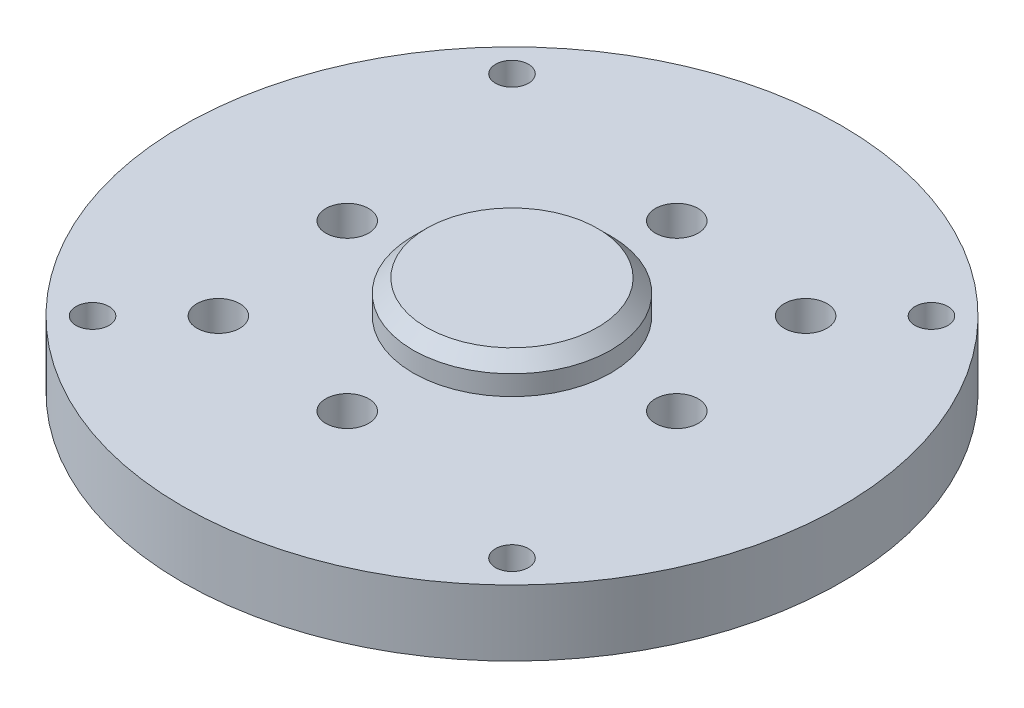
SolidWorks part; units mm, degrees
ref_plane "Front Plane" through (0, 0, 0) normal (0, 0, 1) x (1, 0, 0)
ref_plane "Top Plane" through (0, 0, 0) normal (0, 1, 0) x (1, 0, 0)
ref_plane "Right Plane" through (0, 0, 0) normal (1, 0, 0) x (0, 0, -1)
sketch "Sketch1" plane through (0, 0, 0) normal (0, 1, 0) x (1, 0, 0)
  line L1 (-50, -50) -> (50, -50)
  line L2 (-50, -50) -> (-50, 50)
  line L3 (-50, 50) -> (50, 50)
  line L4 (50, -50) -> (50, 50)
  line L5 (-50, -50) -> (50, 50) construction
  line L6 (-50, 50) -> (50, -50) construction
  point P0 (0, 0)
  dimension "D1" = 100
  dimension "D2" = 100
extrude "Boss-Extrude1" add sketch "Sketch1" along normal blind 10
sketch "Sketch2" plane through (0, 10, 0) normal (0, 1, 0) x (1, 0, 0)
  line L0 (0, 0) -> (-50, 0) construction
  line L1 (-50, 50) -> (-50, -50) construction
  line L2 (0, 0) -> (-25, 0) construction
  line L3 (0, 0) -> (0, 25) construction
  circle A0 centre (-25, 0) radius 3.25
  circle A1 centre (0, 25) radius 3.25
  circle A2 centre (25, 0) radius 3.25
  circle A3 centre (0, -25) radius 3.25
  dimension "D1" = 6.5
  dimension "D2" = 25
  dimension "D4" = 90
  dimension "D5" = 25
  dimension "D3" = 4
extrude "Cut-Extrude1" cut sketch "Sketch2" against normal blind 10
sketch "Sketch3" plane through (0, 10, 0) normal (0, 1, 0) x (1, 0, 0)
  line L0 (-50, 50) -> (-50, -50) construction
  circle A0 centre (0, 0) radius 50
extrude "Cut-Extrude2" cut sketch "Sketch3" against normal blind 10 flip side to cut
sketch "Sketch4" plane through (0, 10, 0) normal (0, 1, 0) x (1, 0, 0)
  line L0 (0, 25) -> (-25, 0)
  line L1 (-25, 0) -> (0, 0)
  line L2 (0, 0) -> (-35.3553, 35.3553)
  circle A0 centre (0, 0) radius 50 construction
  circle A1 centre (-31.8198, 31.8198) radius 2.5
  circle A2 centre (31.8198, 31.8198) radius 2.5
  circle A3 centre (31.8198, -31.8198) radius 2.5
  circle A4 centre (-31.8198, -31.8198) radius 2.5
  point P20 (0, 0)
  dimension "D1" = 5
  dimension "D2" = 45
  dimension "D3" = 4
extrude "Cut-Extrude3" cut sketch "Sketch4" against normal blind 10 contours A1 | A2 | A3 | A4
sketch "Sketch5" plane through (0, 0, 0) normal (0, -1, 0) x (1, 0, 0)
  circle A0 centre (-22.2739, 22.2739) radius 3.25
  circle A1 centre (22.2739, -22.2739) radius 3.25
  dimension "D1" = 6.5
  dimension "D2" = 6.5
extrude "Cut-Extrude4" cut sketch "Sketch5" against normal blind 10
sketch "Sketch6" plane through (0, 0, 0) normal (0, -1, 0) x (1, 0, 0)
  circle A0 centre (25, 0) radius 6.25
  circle A1 centre (25, 0) radius 3.25
  circle A2 centre (25, 0) radius 3.25 construction
  circle A3 centre (22.2739, -22.2739) radius 3.25
  circle A4 centre (22.2739, -22.2739) radius 3.25 construction
  circle A5 centre (0, -25) radius 3.25
  circle A6 centre (0, -25) radius 3.25 construction
  circle A7 centre (-25, 0) radius 3.25
  circle A8 centre (-25, 0) radius 3.25 construction
  circle A9 centre (-22.2739, 22.2739) radius 3.25
  circle A10 centre (-22.2739, 22.2739) radius 3.25 construction
  circle A11 centre (0, 25) radius 3.25
  circle A12 centre (0, 25) radius 3.25 construction
  circle A13 centre (22.2739, -22.2739) radius 6.25
  circle A14 centre (0, -25) radius 6.25
  circle A15 centre (-25, 0) radius 6.25
  circle A16 centre (-22.2739, 22.2739) radius 6.25
  circle A17 centre (0, 25) radius 6.25
  dimension "D1" = 0
  dimension "D2" = 0
  dimension "D3" = 0
  dimension "D4" = 0
  dimension "D5" = 0
  dimension "D6" = 0
  dimension "D7" = 3
extrude "Cut-Extrude5" cut sketch "Sketch6" against normal blind 5
sketch "Sketch7" plane through (0, 10, 0) normal (0, 1, 0) x (1, 0, 0)
  circle A0 centre (0, 0) radius 15
  dimension "D1" = 30
extrude "Boss-Extrude2" add sketch "Sketch7" along normal blind 5
chamfer "Chamfer1" distance 2 angle 45 1 edges at (0, 15, 15)
sketch "Sketch8" plane through (0, 0, 0) normal (0, -1, 0) x (1, 0, 0)
  circle A0 centre (0, 0) radius 34
  dimension "D1" = 68
extrude "Cut-Extrude-Thin1" cut sketch "Sketch8" against normal blind 4 thin thin type mid plane wall 14
ref_point "Point2"
